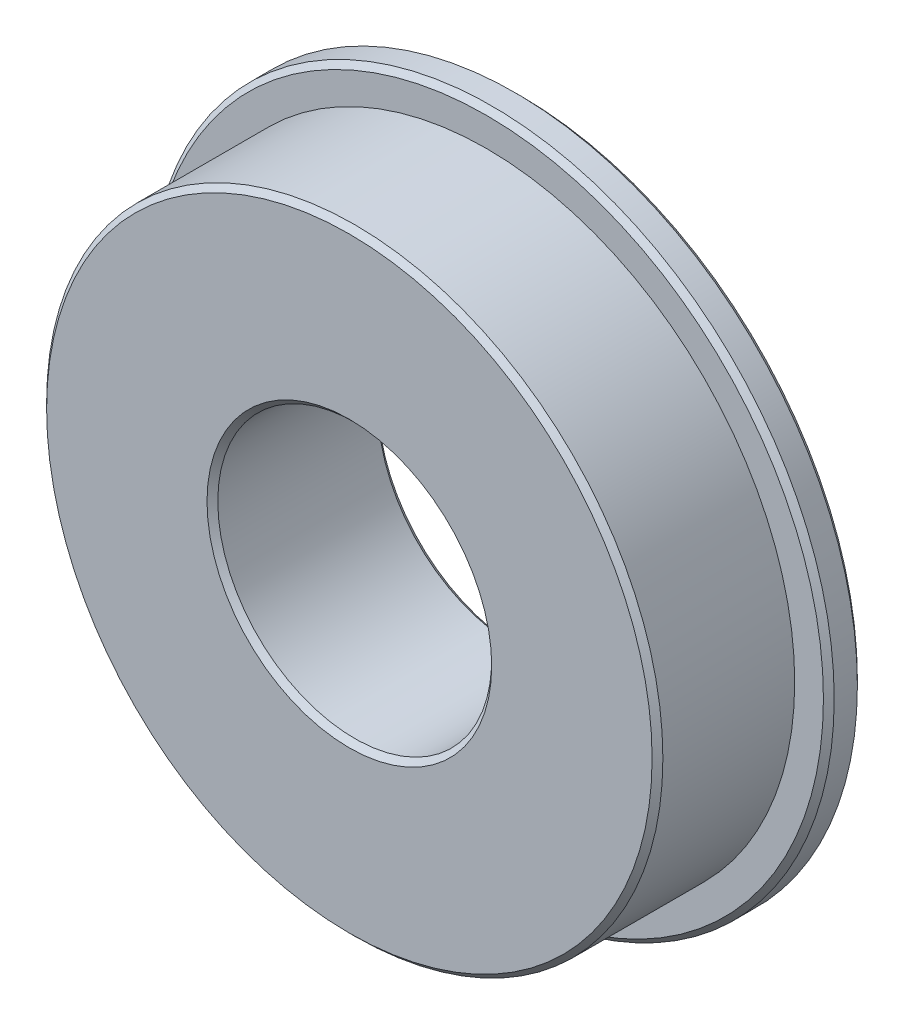
SolidWorks part; units mm, degrees
ref_plane "Front Plane" through (0, 0, 0) normal (0, 0, 1) x (1, 0, 0)
ref_plane "Top Plane" through (0, 0, 0) normal (0, 1, 0) x (1, 0, 0)
ref_plane "Right Plane" through (0, 0, 0) normal (1, 0, 0) x (0, 0, -1)
sketch "Sketch1" plane through (0, 0, 0) normal (0, 1, 0) x (1, 0, 0)
  line L0 (0, 0) -> (0, 6.8644) construction
  line L1 (-14.2875, 6.3627) -> (-14.2875, 0)
  line L2 (-14.2875, 0) -> (-6.35, 0)
  line L3 (-6.35, 0) -> (-6.35, 7.9375)
  line L4 (-6.35, 7.9375) -> (-15.8688, 7.9375)
  line L5 (-15.8688, 7.9375) -> (-15.8688, 6.3627)
  line L6 (-15.8688, 6.3627) -> (-14.2875, 6.3627)
  dimension "D1" = 12.7
  dimension "D2" = 28.575
  dimension "D3" = 7.9375
  dimension "D4" = 6.3627
  dimension "D5" = 31.7375
revolve "Revolve1" add sketch "Sketch1" angle 360 about L0
chamfer "Chamfer1" distance 0.25 angle 45 5 edges at (6.35, 0, 0) (14.2875, 0, 0) (6.35, 0, -7.9375) (15.8688, 0, -7.9375) (15.8688, 0, -6.3627)
